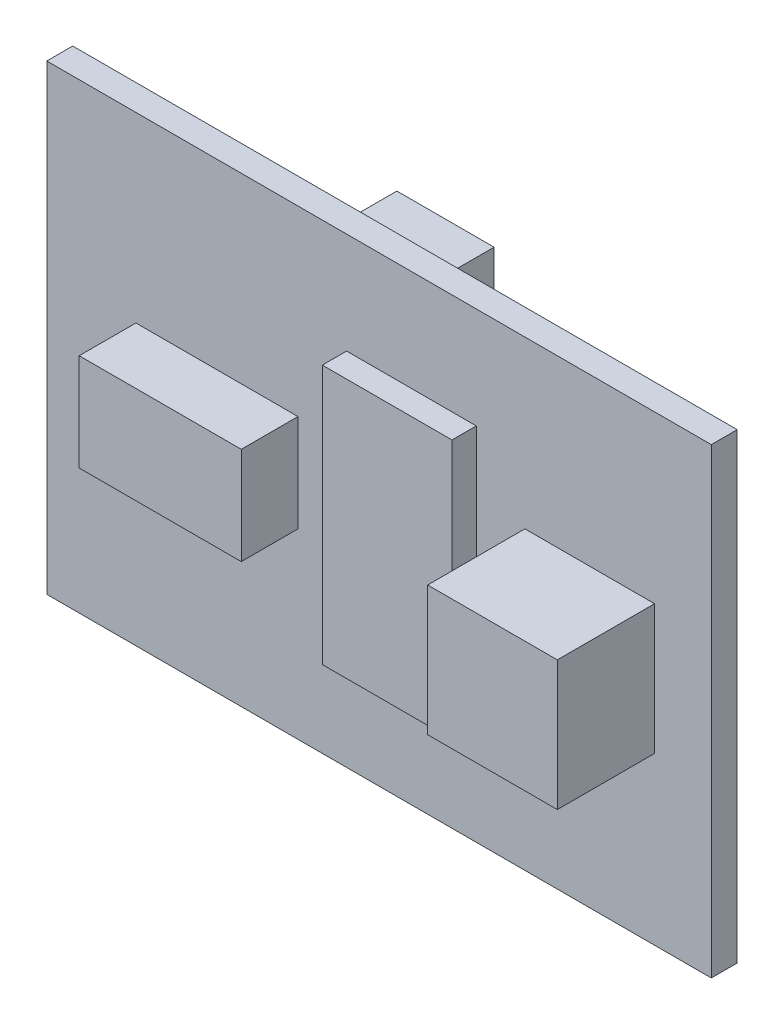
SolidWorks part; units mm, degrees
ref_plane "Front Plane" through (0, 0, 0) normal (0, 0, 1) x (1, 0, 0)
ref_plane "Top Plane" through (0, 0, 0) normal (0, 1, 0) x (1, 0, 0)
ref_plane "Right Plane" through (0, 0, 0) normal (1, 0, 0) x (0, 0, -1)
ref_plane "Plane1" through (0, 0, 13.1) normal (0, 0, 1) x (1, 0, 0)
sketch "Sketch1" plane through (0, 0, 13.1) normal (0, 0, 1) x (1, 0, 0)
  line L1 (-30.5, -10.75) -> (10.5, -10.75)
  line L2 (-30.5, -10.75) -> (-30.5, 17.75)
  line L3 (-30.5, 17.75) -> (10.5, 17.75)
  line L4 (10.5, -10.75) -> (10.5, 17.75)
  line L5 (-30.5, -10.75) -> (10.5, 17.75) construction
  line L6 (-30.5, 17.75) -> (10.5, -10.75) construction
  point P0 (-10, 3.5)
extrude "Boss-Extrude1" add sketch "Sketch1" along normal blind 1.6
ref_plane "Plane2" through (0, 0, 10.6) normal (0, 0, 1) x (1, 0, 0)
sketch "Sketch2" plane through (0, 0, 10.6) normal (0, 0, 1) x (1, 0, 0)
  line L1 (-13, -10.5) -> (-7, -10.5)
  line L2 (-13, -10.5) -> (-13, 17.5)
  line L3 (-13, 17.5) -> (-7, 17.5)
  line L4 (-7, -10.5) -> (-7, 17.5)
  line L5 (-13, -10.5) -> (-7, 17.5) construction
  line L6 (-13, 17.5) -> (-7, -10.5) construction
  point P0 (-10, 3.5)
extrude "Boss-Extrude2" add sketch "Sketch2" along normal blind 2.5
ref_plane "Plane3" through (0, 0, 14.7) normal (0, 0, 1) x (1, 0, 0)
sketch "Sketch3" plane through (0, 0, 14.7) normal (0, 0, 1) x (1, 0, 0)
  line L1 (-1, -0.5) -> (7, -0.5)
  line L2 (-1, -0.5) -> (-1, 7.5)
  line L3 (-1, 7.5) -> (7, 7.5)
  line L4 (7, -0.5) -> (7, 7.5)
  line L5 (-1, -0.5) -> (7, 7.5) construction
  line L6 (-1, 7.5) -> (7, -0.5) construction
  point P0 (3, 3.5)
extrude "Boss-Extrude3" add sketch "Sketch3" along normal blind 6
sketch "Sketch4" plane through (0, 0, 14.7) normal (0, 0, 1) x (1, 0, 0)
  line L1 (-25, 0.5) -> (-15, 0.5)
  line L2 (-25, 0.5) -> (-25, 6.5)
  line L3 (-25, 6.5) -> (-15, 6.5)
  line L4 (-15, 0.5) -> (-15, 6.5)
  line L5 (-25, 0.5) -> (-15, 6.5) construction
  line L6 (-25, 6.5) -> (-15, 0.5) construction
  point P0 (-20, 3.5)
extrude "Boss-Extrude4" add sketch "Sketch4" along normal blind 3.5
sketch "Sketch5" plane through (0, 0, 14.7) normal (0, 0, 1) x (1, 0, 0)
  line L1 (-12, -4.5) -> (-4, -4.5)
  line L2 (-12, -4.5) -> (-12, 11.5)
  line L3 (-12, 11.5) -> (-4, 11.5)
  line L4 (-4, -4.5) -> (-4, 11.5)
  line L5 (-12, -4.5) -> (-4, 11.5) construction
  line L6 (-12, 11.5) -> (-4, -4.5) construction
  point P0 (-8, 3.5)
extrude "Boss-Extrude5" add sketch "Sketch5" along normal blind 1.5
